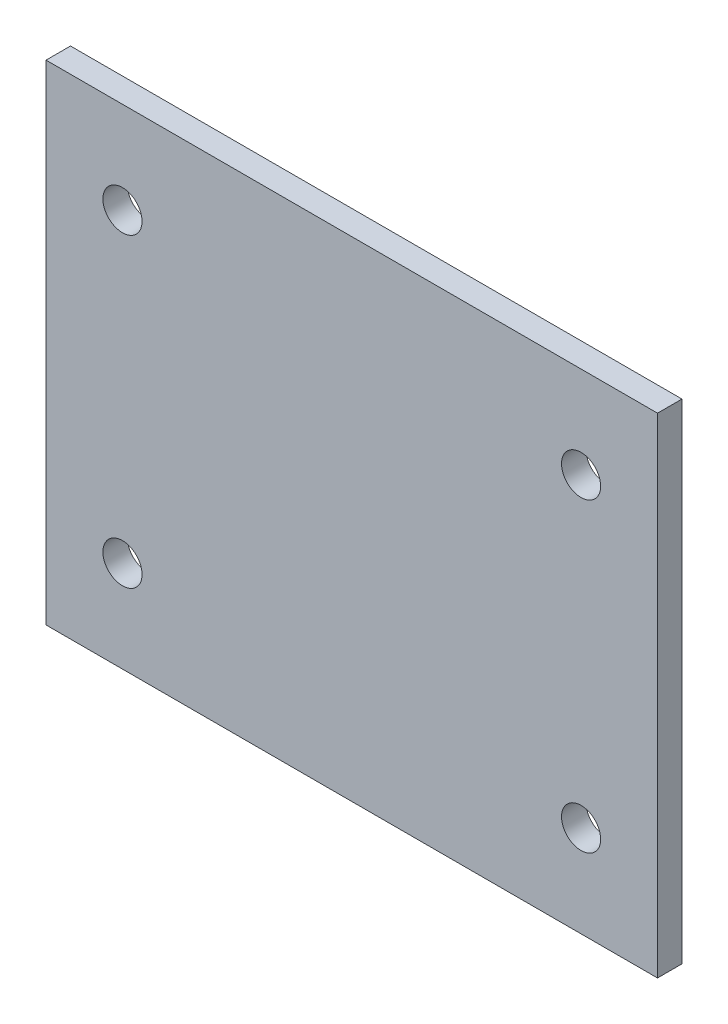
SolidWorks part; units mm, degrees
ref_plane "Piano frontale" through (0, 0, 0) normal (0, 0, 1) x (1, 0, 0)
ref_plane "Piano superiore" through (0, 0, 0) normal (0, 1, 0) x (1, 0, 0)
ref_plane "Piano destro" through (0, 0, 0) normal (1, 0, 0) x (0, 0, -1)
sketch "Schizzo1" plane through (0, 0, 0) normal (0, 0, 1) x (1, 0, 0)
  line L1 (-37.5, 25) -> (37.5, 25)
  line L2 (-37.5, 25) -> (-37.5, -25)
  line L3 (-37.5, -25) -> (37.5, -25)
  line L4 (37.5, 25) -> (37.5, -25)
  line L5 (-37.5, 25) -> (37.5, -25) construction
  line L6 (-37.5, -25) -> (37.5, 25) construction
  line L7 (-50, 40) -> (50, 40)
  line L8 (-50, 40) -> (-50, -40)
  line L9 (-50, -40) -> (50, -40)
  line L10 (50, 40) -> (50, -40)
  line L11 (-50, 40) -> (50, -40) construction
  line L12 (-50, -40) -> (50, 40) construction
  circle A0 centre (-37.5, 25) radius 3.2
  circle A1 centre (37.5, 25) radius 3.2
  circle A2 centre (37.5, -25) radius 3.2
  circle A3 centre (-37.5, -25) radius 3.2
  point P0 (0, 0)
  point P10 (0, 0)
  dimension "D1" = 6.4
  dimension "D2" = 75
  dimension "D3" = 50
  dimension "D4" = 100
  dimension "D5" = 80
extrude "Estrusione-Estrusione1" add sketch "Schizzo1" along normal blind 4 contours L10 L7 L8 L9 A3 L2 A0 L1 A1 L4 A2 L3 | A3 L3 A2 L4 A1 L1 A0 L2
